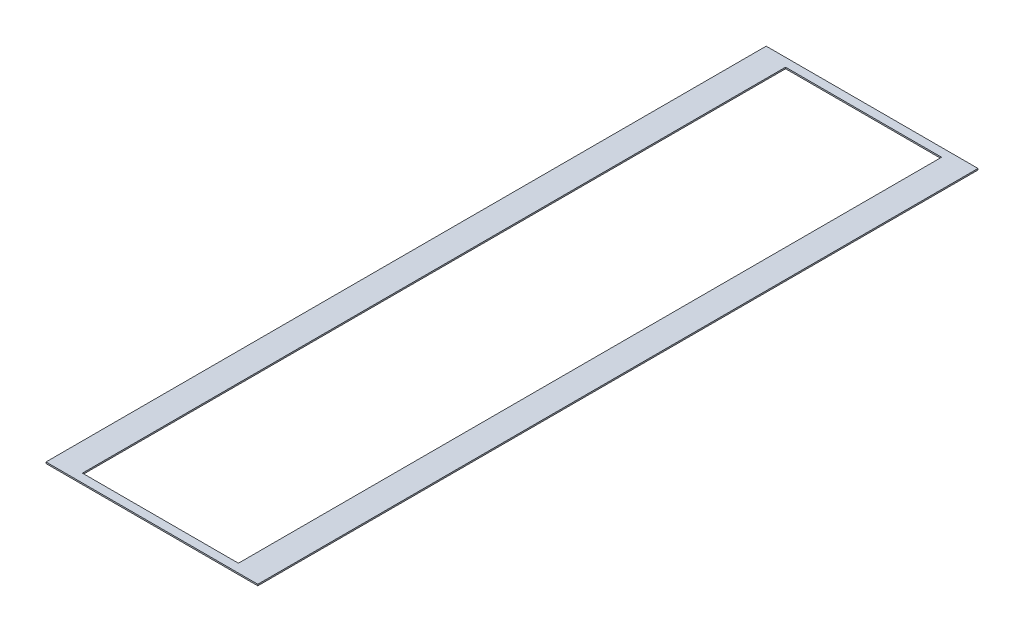
SolidWorks part; units mm, degrees
ref_plane "Front Plane" through (0, 0, 0) normal (0, 0, 1) x (1, 0, 0)
ref_plane "Top Plane" through (0, 0, 0) normal (0, 1, 0) x (1, 0, 0)
ref_plane "Right Plane" through (0, 0, 0) normal (1, 0, 0) x (0, 0, -1)
sketch "Sketch1" plane through (0, 0, 0) normal (0, 1, 0) x (1, 0, 0)
  line L1 (-75, 255) -> (75, 255)
  line L2 (-75, 255) -> (-75, -255)
  line L3 (-75, -255) -> (75, -255)
  line L4 (75, 255) -> (75, -255)
  line L5 (-75, 255) -> (75, -255) construction
  line L6 (-75, -255) -> (75, 255) construction
  point P0 (0, 0)
  dimension "D1" = 150
  dimension "D2" = 510
extrude "Boss-Extrude1" add sketch "Sketch1" along normal blind 1
sketch "Sketch2" plane through (0, 1, 0) normal (0, 1, 0) x (1, 0, 0)
  line L1 (-55.2351, 248.9757) -> (55.2351, 248.9757)
  line L2 (-55.2351, 248.9757) -> (-55.2351, -248.9757)
  line L3 (-55.2351, -248.9757) -> (55.2351, -248.9757)
  line L4 (55.2351, 248.9757) -> (55.2351, -248.9757)
  line L5 (-55.2351, 248.9757) -> (55.2351, -248.9757) construction
  line L6 (-55.2351, -248.9757) -> (55.2351, 248.9757) construction
  point P0 (0, 0)
extrude "Cut-Extrude1" cut sketch "Sketch2" against normal blind 1
